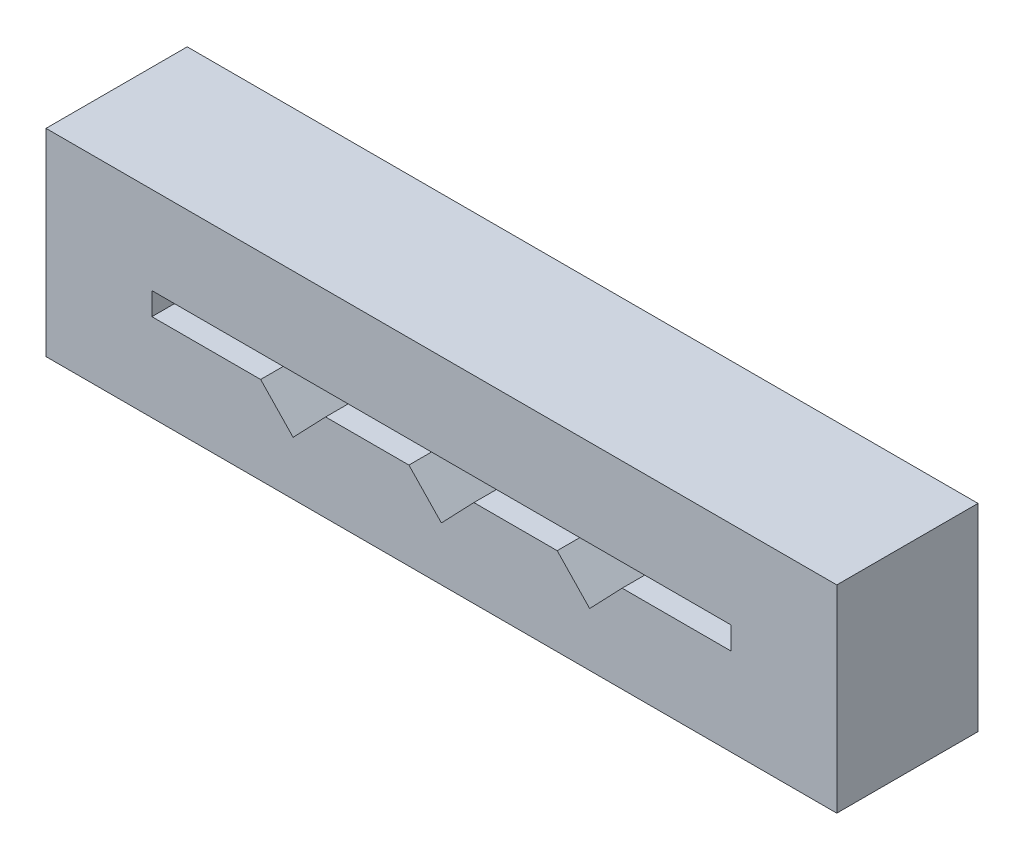
SolidWorks part; units mm, degrees
material "Сосна"
ref_plane "Front" through (0, 0, 0) normal (0, 0, 1) x (1, 0, 0)
ref_plane "Top" through (0, 0, 0) normal (0, 1, 0) x (1, 0, 0)
ref_plane "Right" through (0, 0, 0) normal (1, 0, 0) x (0, 0, -1)
sketch "Эскиз1" plane through (0, 66.7543, 0) normal (0, 0, 1) x (-1, 0, 0)
  line L1 (14, 63.2543) -> (-14, 70.2543) construction
  line L31 (-14, 63.2543) -> (14, 63.2543)
  line L32 (-14, 63.2543) -> (-14, 70.2543)
  line L33 (-14, 70.2543) -> (14, 70.2543)
  line L34 (14, 63.2543) -> (14, 70.2543)
  line L35 (-14, 63.2543) -> (14, 70.2543) construction
  point P12 (0, 66.7543)
  point P22 (0, 66.7543)
  point P26 (0, 66.7543)
  dimension "D1" = 7
  dimension "D2" = 28
extrude "Бобышка-Вытянуть1" add sketch "Эскиз1" along normal blind 5
sketch "Эскиз4" plane through (0, 0, 0) normal (0, 0, -1) x (-1, 0, 0)
  line L0 (-10.25, 0.4) -> (-10.25, -3.5) construction
  line L1 (-10.25, -0.4) -> (-10.25, 0.4)
  line L2 (-10.25, -0.4) -> (10.25, -0.4) construction
  line L3 (10.25, -0.4) -> (10.25, 0.4)
  line L4 (-10.25, 0.4) -> (10.25, 0.4)
  line L5 (-10.25, -0.4) -> (10.25, 0.4) construction
  line L6 (10.25, -0.4) -> (-10.25, 0.4) construction
  line L7 (10.25, -0.4) -> (10.25, 3.5) construction
  line L9 (-6.4, -0.4) -> (-5.25, -1.6)
  line L10 (-5.25, -1.6) -> (-4.1, -0.4)
  line L11 (-4.1, -0.4) -> (-1.15, -0.4)
  line L12 (-1.15, -0.4) -> (0, -1.6)
  line L13 (0, -1.6) -> (1.15, -0.4)
  line L14 (1.15, -0.4) -> (4.1, -0.4)
  line L15 (4.1, -0.4) -> (5.25, -1.6)
  line L16 (5.25, -1.6) -> (6.4, -0.4)
  line L18 (0, 0) -> (0, -1.6) construction
  line L19 (14, -3.5) -> (-14, -3.5) construction
  line L20 (6.4, -0.4) -> (10.25, -0.4)
  line L21 (-14, 3.5) -> (14, 3.5) construction
  line L22 (-6.4, -0.4) -> (-10.25, -0.4)
  point P4 (0, 0)
  point P28 (0, -0.4)
  dimension "D1" = 0.8
  dimension "D2" = 20.5
  dimension "D3" = 2.3
  dimension "D4" = 1.2
  dimension "D5" = 10.5
extrude "Вырез-Вытянуть1" cut sketch "Эскиз4" against normal through all
chamfer "Фаска1" distance 0.5 angle 45 7 edges at (-2.625, -0.4, 0) (2.625, -0.4, 0) (8.325, -0.4, 0) (10.25, 0, 0) (-8.325, -0.4, 0) (-10.25, 0, 0) (0, 0.4, 0)
